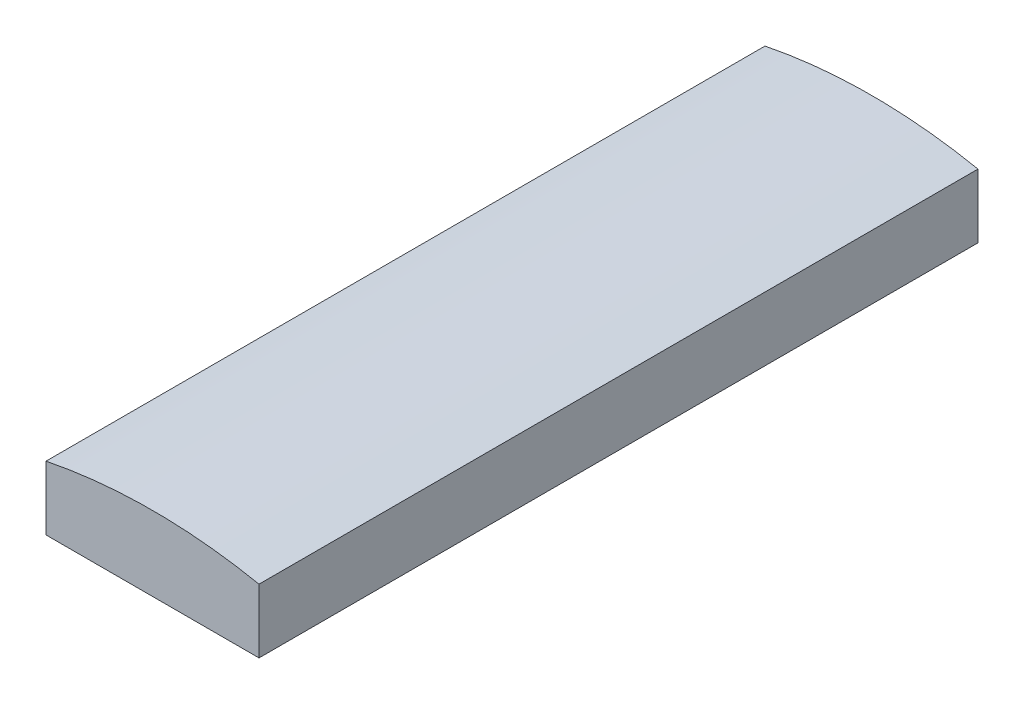
SolidWorks part; units mm, degrees
ref_plane "Ön Düzlem" through (0, 0, 0) normal (0, 0, 1) x (1, 0, 0)
ref_plane "Üst Düzlem" through (0, 0, 0) normal (0, 1, 0) x (1, 0, 0)
ref_plane "Sağ Düzlem" through (0, 0, 0) normal (1, 0, 0) x (0, 0, -1)
sketch "Sketch1" plane through (0, 0, 0) normal (0, 0, 1) x (1, 0, 0)
  line L0 (0, 0) -> (20, 0)
  line L1 (10, 0) -> (10, 7)
  line L2 (0, 0) -> (0, 6)
  line L3 (20, 0) -> (20, 6)
  line L4 (10, 7) -> (24.6389, 7) construction
  arc A0 (0, 6) -> (20, 6) centre (10, -43.5) cw
  point P8 (10, 3.5)
  dimension "D1" = 6
  dimension "D5" = 7
  dimension "D6" = 50.5
  dimension "D2" = 20
  dimension "D3" = 7
  dimension "D4" = 6
extrude "Boss-Extrude1" add sketch "Sketch1" along normal blind 67.5 contours A0 L3 L0 L2
